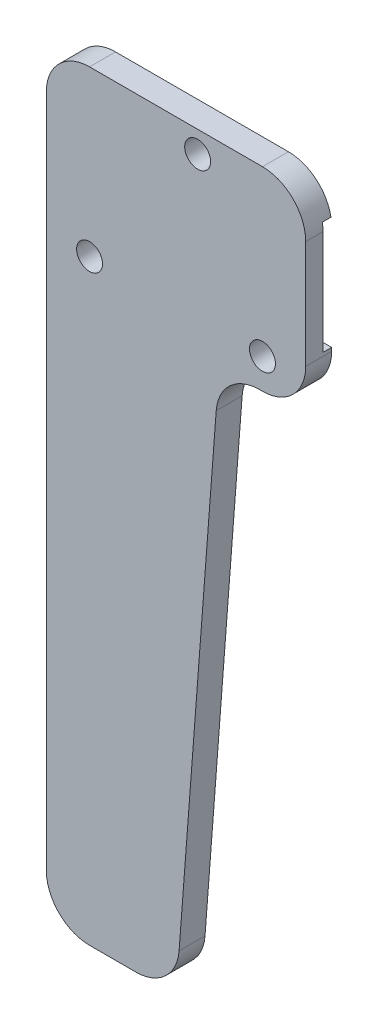
SolidWorks part; units mm, degrees
material "Acrílico (Impacto medio-alto)"
ref_plane "Alzado" through (0, 0, 0) normal (0, 0, 1) x (1, 0, 0)
ref_plane "Planta" through (0, 0, 0) normal (0, 1, 0) x (1, 0, 0)
ref_plane "Vista lateral" through (0, 0, 0) normal (1, 0, 0) x (0, 0, -1)
sketch "Croquis1" plane through (0, 0, 0) normal (0, 0, 1) x (1, 0, 0)
  line L0 (0, -5) -> (0, -83)
  line L1 (5, 0) -> (25, 0)
  line L2 (30, -5) -> (30, -17.5)
  line L3 (25, -22.5) -> (24.6329, -22.5)
  line L4 (19.6474, -27.1194) -> (15.3526, -83.3806)
  line L5 (10.3671, -88) -> (5, -88)
  arc A0 (0, -83) -> (5, -88) centre (5, -83) ccw
  arc A1 (15.3526, -83.3806) -> (10.3671, -88) centre (10.3671, -83) cw
  arc A2 (24.6329, -22.5) -> (19.6474, -27.1194) centre (24.6329, -27.5) ccw
  arc A3 (30, -17.5) -> (25, -22.5) centre (25, -17.5) cw
  arc A4 (25, 0) -> (30, -5) centre (25, -5) cw
  arc A5 (0, -5) -> (5, 0) centre (5, -5) cw
  circle A6 centre (17.5, -2.5) radius 1.5
  circle A7 centre (5, -19) radius 1.5
  circle A8 centre (25, -19) radius 1.5
  point P9 (0, -88)
  point P12 (15, -88)
  point P15 (20, -22.5)
  point P18 (30, -22.5)
  point P21 (30, 0)
  point P24 (0, 0)
  dimension "D6" = 5
  dimension "D7" = 5
  dimension "D8" = 5
  dimension "D9" = 5
  dimension "D10" = 5
  dimension "D11" = 5
  dimension "D12" = 3
  dimension "D13" = 2.5
  dimension "D14" = 12.5
  dimension "D15" = 3
  dimension "D16" = 19
  dimension "D17" = 5
  dimension "D18" = 3
  dimension "D1" = 88
  dimension "D2" = 30
  dimension "D3" = 22.5
  dimension "D4" = 10
  dimension "D5" = 15
extrude "Saliente-Extruir1" add sketch "Croquis1" against normal blind 3
sketch "Croquis2" plane through (0, 0, -3) normal (0, 0, -1) x (-1, 0, 0)
  line L0 (-30, -17.5) -> (-30, -5) construction
  line L1 (-30, -17.1) -> (0, -17.1)
  line L2 (-30, -17.1) -> (-30, -4.1)
  line L3 (-30, -4.1) -> (0, -4.1)
  line L4 (0, -17.1) -> (0, -4.1)
  line L5 (0, -5) -> (0, -83) construction
  circle A1 centre (-17.5, -2.5) radius 1.5 construction
  point P8 (-30, -5.7376)
  point P9 (0, 0)
  dimension "D1" = 13
  dimension "D2" = 1.6
extrude "Cortar-Extruir2" cut sketch "Croquis2" against normal blind 1
